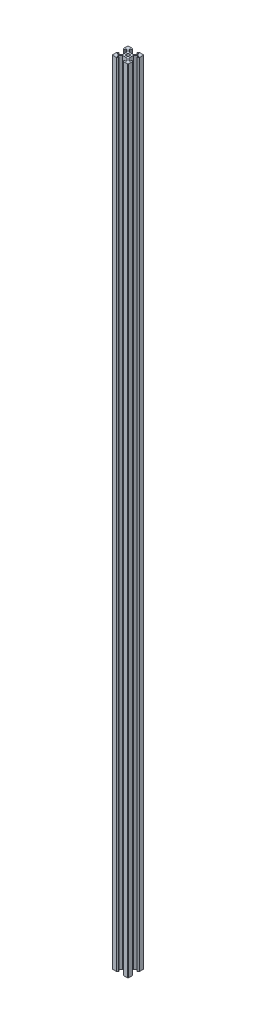
SolidWorks part; units mm, degrees
ref_plane "Front Plane" through (0, 0, 0) normal (0, 0, 1) x (1, 0, 0)
ref_plane "Top Plane" through (0, 0, 0) normal (0, 1, 0) x (1, 0, 0)
ref_plane "Right Plane" through (0, 0, 0) normal (1, 0, 0) x (0, 0, -1)
sketch "Sketch1" plane through (0, 0, 0) normal (1, 0, 0) x (0, 0, -1)
  line L0 (0, 0) -> (0, 1000)
  dimension "D1" = 1000
other "Vslot2020 2020(5)"
ref_plane "Plane5" through (0, 0, 0) normal (0, 1, 0) x (0, 0, 1)
sketch "Sketch2" plane through (0, 0, 0) normal (0, 1, 0) x (0, 0, 1)
  line L58 (13.9, 7.1491) -> (13.9, 12.8445)
  line L59 (13.9, 12.8445) -> (16.5585, 15.4922)
  line L60 (16.5585, 15.4922) -> (16.5507, 15.5)
  line L61 (16.5507, 15.5) -> (18.2, 15.5)
  line L62 (18.2, 15.5) -> (18.2, 13.12)
  line L63 (18.2, 13.12) -> (18.5344, 13.12)
  line L64 (18.5344, 13.12) -> (20, 14.58)
  line L65 (20, 14.58) -> (20, 19.5)
  line L66 (19.5, 20) -> (14.575, 20)
  line L67 (14.575, 20) -> (13.12, 18.545)
  line L68 (13.12, 18.545) -> (13.12, 18.2)
  line L69 (13.12, 18.2) -> (15.5, 18.2)
  line L70 (15.5, 18.2) -> (15.5, 16.555)
  line L71 (15.5, 16.555) -> (12.8341, 13.9)
  line L72 (12.8341, 13.9) -> (7.155, 13.9)
  line L73 (7.155, 13.9) -> (4.5, 16.555)
  line L74 (4.5, 16.555) -> (4.5, 18.2)
  line L75 (4.5, 18.2) -> (6.875, 18.2)
  line L76 (6.875, 18.2) -> (6.875, 18.545)
  line L77 (6.875, 18.545) -> (5.42, 20)
  line L78 (5.42, 20) -> (0.5, 20)
  line L79 (0, 19.5) -> (0, 14.58)
  line L80 (0, 14.58) -> (1.46, 13.12)
  line L81 (1.46, 13.12) -> (1.8, 13.12)
  line L82 (1.8, 13.12) -> (1.8, 15.5)
  line L83 (1.8, 15.5) -> (3.445, 15.5)
  line L84 (3.445, 15.5) -> (3.4393, 15.4943)
  line L85 (3.4393, 15.4943) -> (6.0943, 12.8393)
  line L86 (6.0943, 12.8393) -> (6.1, 12.845)
  line L87 (6.1, 12.845) -> (6.1, 7.1491)
  line L88 (6.1, 7.1491) -> (3.4393, 4.5)
  line L89 (3.4393, 4.5) -> (1.8, 4.5)
  line L90 (1.8, 4.5) -> (1.8, 6.88)
  line L91 (1.8, 6.88) -> (1.46, 6.88)
  line L92 (1.46, 6.88) -> (0, 5.42)
  line L93 (0, 5.42) -> (0, 0.5)
  line L94 (0.5, 0) -> (5.42, 0)
  line L95 (5.42, 0) -> (6.875, 1.455)
  line L96 (6.875, 1.455) -> (6.875, 1.8)
  line L97 (6.875, 1.8) -> (4.5, 1.8)
  line L98 (4.5, 1.8) -> (4.5, 3.4393)
  line L99 (4.5, 3.4393) -> (7.1583, 6.0861)
  line L100 (7.1583, 6.0861) -> (7.1445, 6.1)
  line L101 (7.1445, 6.1) -> (12.8546, 6.1)
  line L102 (12.8546, 6.1) -> (12.8412, 6.0865)
  line L103 (12.8412, 6.0865) -> (15.4997, 3.4375)
  line L104 (15.4997, 3.4375) -> (15.5, 3.4377)
  line L105 (15.5, 3.4377) -> (15.5, 1.8)
  line L106 (15.5, 1.8) -> (13.12, 1.8)
  line L107 (13.12, 1.8) -> (13.12, 1.455)
  line L108 (13.12, 1.455) -> (14.575, 0)
  line L109 (14.575, 0) -> (19.5, 0)
  line L110 (20, 0.5) -> (20, 5.42)
  line L111 (20, 5.42) -> (18.6069, 6.88)
  line L112 (18.6069, 6.88) -> (18.2, 6.88)
  line L113 (18.2, 6.88) -> (18.2, 4.5)
  line L114 (18.2, 4.5) -> (16.5585, 4.5)
  line L115 (16.5585, 4.5) -> (13.9, 7.1491)
  line L116 (13.9, 7.1491) -> (13.9, 12.8445)
  line L117 (13.9, 12.8445) -> (16.5585, 15.4922)
  line L118 (16.5585, 15.4922) -> (16.5507, 15.5)
  line L119 (16.5507, 15.5) -> (18.2, 15.5)
  line L120 (18.2, 15.5) -> (18.2, 13.12)
  line L121 (18.2, 13.12) -> (18.5344, 13.12)
  line L122 (18.5344, 13.12) -> (20, 14.58)
  line L123 (20, 14.58) -> (20, 19.5)
  line L124 (19.5, 20) -> (14.575, 20)
  line L125 (14.575, 20) -> (13.12, 18.545)
  line L126 (13.12, 18.545) -> (13.12, 18.2)
  line L127 (13.12, 18.2) -> (15.5, 18.2)
  line L128 (15.5, 18.2) -> (15.5, 16.555)
  line L129 (15.5, 16.555) -> (12.8341, 13.9)
  line L130 (12.8341, 13.9) -> (7.155, 13.9)
  line L131 (7.155, 13.9) -> (4.5, 16.555)
  line L132 (4.5, 16.555) -> (4.5, 18.2)
  line L133 (4.5, 18.2) -> (6.875, 18.2)
  line L134 (6.875, 18.2) -> (6.875, 18.545)
  line L135 (6.875, 18.545) -> (5.42, 20)
  line L136 (5.42, 20) -> (0.5, 20)
  line L137 (0, 19.5) -> (0, 14.58)
  line L138 (0, 14.58) -> (1.46, 13.12)
  line L139 (1.46, 13.12) -> (1.8, 13.12)
  line L140 (1.8, 13.12) -> (1.8, 15.5)
  line L141 (1.8, 15.5) -> (3.445, 15.5)
  line L142 (3.445, 15.5) -> (3.4393, 15.4943)
  line L143 (3.4393, 15.4943) -> (6.0943, 12.8393)
  line L144 (6.0943, 12.8393) -> (6.1, 12.845)
  line L145 (6.1, 12.845) -> (6.1, 7.1491)
  line L146 (6.1, 7.1491) -> (3.4393, 4.5)
  line L147 (3.4393, 4.5) -> (1.8, 4.5)
  line L148 (1.8, 4.5) -> (1.8, 6.88)
  line L149 (1.8, 6.88) -> (1.46, 6.88)
  line L150 (1.46, 6.88) -> (0, 5.42)
  line L151 (0, 5.42) -> (0, 0.5)
  line L152 (0.5, 0) -> (5.42, 0)
  line L153 (5.42, 0) -> (6.875, 1.455)
  line L154 (6.875, 1.455) -> (6.875, 1.8)
  line L155 (6.875, 1.8) -> (4.5, 1.8)
  line L156 (4.5, 1.8) -> (4.5, 3.4393)
  line L157 (4.5, 3.4393) -> (7.1583, 6.0861)
  line L158 (7.1583, 6.0861) -> (7.1445, 6.1)
  line L159 (7.1445, 6.1) -> (12.8546, 6.1)
  line L160 (12.8546, 6.1) -> (12.8412, 6.0865)
  line L161 (12.8412, 6.0865) -> (15.4997, 3.4375)
  line L162 (15.4997, 3.4375) -> (15.5, 3.4377)
  line L163 (15.5, 3.4377) -> (15.5, 1.8)
  line L164 (15.5, 1.8) -> (13.12, 1.8)
  line L165 (13.12, 1.8) -> (13.12, 1.455)
  line L166 (13.12, 1.455) -> (14.575, 0)
  line L167 (14.575, 0) -> (19.5, 0)
  line L168 (20, 0.5) -> (20, 5.42)
  line L169 (20, 5.42) -> (18.6069, 6.88)
  line L170 (18.6069, 6.88) -> (18.2, 6.88)
  line L171 (18.2, 6.88) -> (18.2, 4.5)
  line L172 (18.2, 4.5) -> (16.5585, 4.5)
  line L173 (16.5585, 4.5) -> (13.9, 7.1491)
  circle A0 centre (10, 10) radius 2.0746 construction
  circle A1 centre (10, 10) radius 2.0746
  arc A4 (20, 19.5) -> (19.5, 20) centre (19.5, 19.5) ccw
  arc A5 (0.5, 20) -> (0, 19.5) centre (0.5, 19.5) ccw
  arc A6 (0, 0.5) -> (0.5, 0) centre (0.5, 0.5) ccw
  arc A7 (19.5, 0) -> (20, 0.5) centre (19.5, 0.5) ccw
  arc A8 (20, 19.5) -> (19.5, 20) centre (19.5, 19.5) ccw
  arc A9 (0.5, 20) -> (0, 19.5) centre (0.5, 19.5) ccw
  arc A10 (0, 0.5) -> (0.5, 0) centre (0.5, 0.5) ccw
  arc A11 (19.5, 0) -> (20, 0.5) centre (19.5, 0.5) ccw
  point P16 (0, 0)
  dimension "D1" = 0
ref_plane "Plane6" through (0, 0, 9.9946) normal (0, 0, 1) x (1, 0, 0)
sketch "Sketch3" plane through (0, 0, 9.9946) normal (0, 0, 1) x (1, 0, 0)
  line L0 (9.9968, 0) -> (9.9968, 1000)
  line L1 (7.1491, 0) -> (12.8445, 0) construction
  line L2 (7.1491, 1000) -> (12.8445, 1000) construction
ref_plane "Plane7" through (6.1, 0, 0) normal (-1, 0, 0) x (0, 0, 1)
